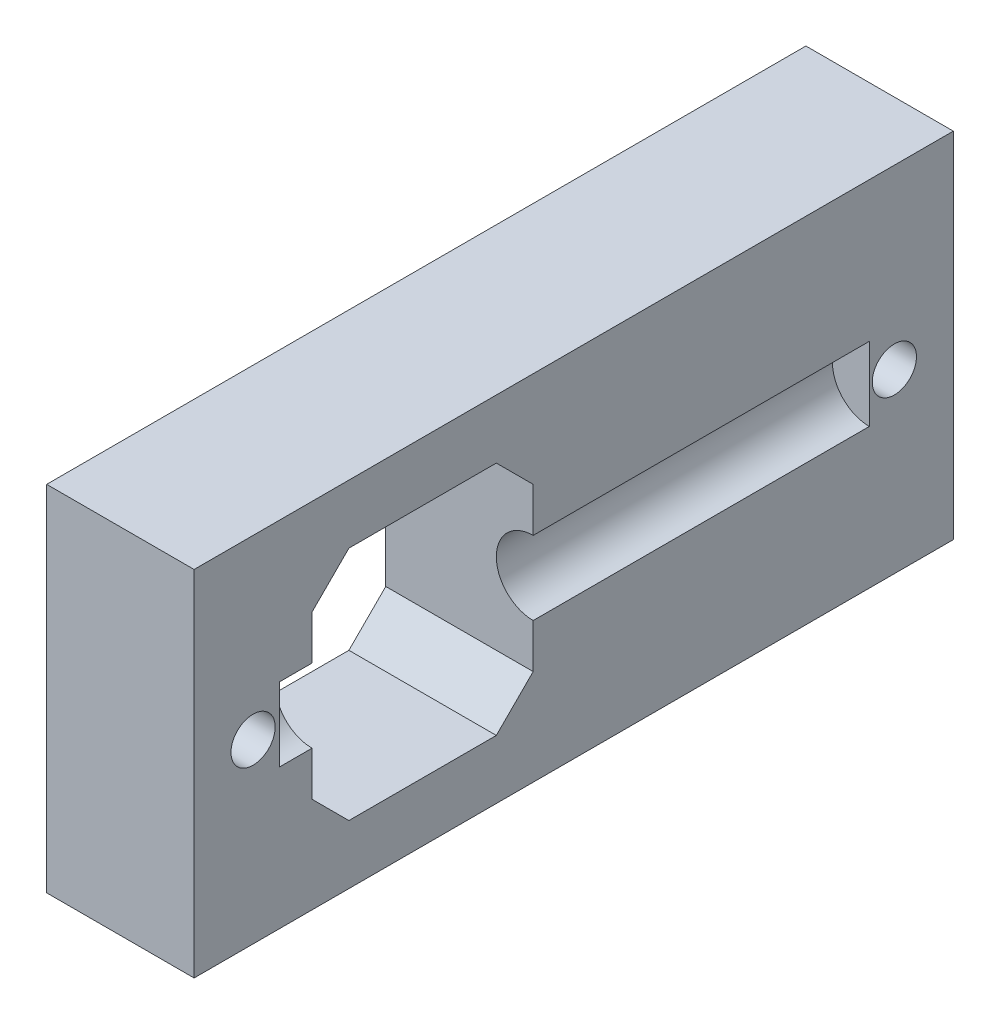
SolidWorks part; units mm, degrees
ref_plane "前基準面" through (0, 0, 0) normal (0, 0, 1) x (1, 0, 0)
ref_plane "上基準面" through (0, 0, 0) normal (0, 1, 0) x (1, 0, 0)
ref_plane "右基準面" through (0, 0, 0) normal (1, 0, 0) x (0, 0, -1)
sketch "草圖1" plane through (0, 0, 0) normal (0, 0, 1) x (1, 0, 0)
  line L1 (-21, 21) -> (21, 21)
  line L2 (-21, 21) -> (-21, -21)
  line L3 (-21, -21) -> (21, -21)
  line L4 (21, 21) -> (21, -21)
  point P4 (0, 21)
  point P6 (-21, 0)
  dimension "D1" = 42
  dimension "D2" = 42
extrude "填料-伸長1" add sketch "草圖1" along normal blind 40
chamfer "導角1" distance 5 angle 45 4 edges at (-21, -21, 20) (21, -21, 20) (21, 21, 20) (-21, 21, 20)
sketch "草圖4" plane through (0, 0, 40) normal (0, 0, 1) x (1, 0, 0)
  line L0 (-21, 16) -> (-21, -16) construction
  line L1 (16, 21) -> (-16, 21) construction
  line L2 (0, 21) -> (0, -21) construction
  line L3 (-16, -21) -> (16, -21) construction
  line L4 (0, -21) -> (21, 0) construction
  line L5 (21, -16) -> (21, 16) construction
  line L6 (21, 0) -> (-21, 0) construction
  circle A0 centre (-15.5, 15.5) radius 1.75
  circle A1 centre (-15.5, -15.5) radius 1.75
  circle A2 centre (15.5, -15.5) radius 1.75
  circle A3 centre (15.5, 15.5) radius 1.75
  dimension "D1" = 3.5
  dimension "D2" = 5.5
  dimension "D3" = 5.5
  dimension "D4" = 31
extrude "除料-伸長1" cut sketch "草圖4" against normal blind 3
sketch "草圖5" plane through (-21, 0, 0) normal (-1, 0, 0) x (0, 0, 1)
  line L0 (40, 16) -> (40, -16) construction
  line L1 (40, 12) -> (66, 12)
  line L2 (40, 12) -> (40, -12)
  line L3 (40, -12) -> (66, -12)
  line L4 (66, 12) -> (66, -12)
  line L5 (0, 0) -> (66, 0) construction
  line L7 (43, 8) -> (58, 8)
  line L8 (43, 8) -> (43, -8)
  line L9 (43, -8) -> (58, -8)
  line L10 (58, 8) -> (58, -8)
  dimension "D1" = 24
  dimension "D2" = 26
  dimension "D3" = 4
  dimension "D4" = 8
  dimension "D5" = 3
  dimension "D6" = 4
extrude "填料-伸長2" add sketch "草圖5" against normal blind 21 separate body
sketch "草圖7" plane through (21, 0, 0) normal (1, 0, 0) x (0, 0, -1)
  line L0 (0, -16) -> (0, 16) construction
  line L1 (-40, 12) -> (0, 12)
  line L2 (-40, 12) -> (-40, -12)
  line L3 (-40, -12) -> (0, -12)
  line L4 (0, 12) -> (0, -12)
extrude "除料-伸長3" cut sketch "草圖7" against normal blind 21
sketch "草圖6" plane through (0, 0, 0) normal (1, 0, 0) x (0, 0, -1)
  line L3 (-58, 8) -> (-66, 8) construction
  line L4 (-66, -12) -> (-66, 12) construction
  line L5 (-58, -8) -> (-66, -8) construction
  line L6 (-62, 8) -> (-62, -8) construction
  line L7 (-60.25, 0) -> (-20.25, 0) construction
  circle A0 centre (-62, 0) radius 3
  circle A1 centre (-62, 0) radius 1.75 construction
  circle A2 centre (-18.5, 0) radius 1.75 construction
  circle A3 centre (-18.5, 0) radius 3
  dimension "D1" = 6
  dimension "D4" = 3.5
  dimension "D3" = 3.5
  dimension "D5" = 6
  dimension "D2" = 40
extrude "除料-伸長2" cut sketch "草圖6" against normal blind 10
chamfer "導角2" distance 2.5 angle 45 4 edges at (-10.5, -8, 43) (-10.5, 8, 43) (-10.5, -8, 58) (-10.5, 8, 58)
sketch "草圖8" plane through (0, 0, 0) normal (1, 0, 0) x (0, 0, -1)
  line L0 (-40, -12) -> (0, -12) construction
  line L1 (-66, 12) -> (-14.5, 12)
  line L2 (-66, 12) -> (-66, -12)
  line L3 (-66, -12) -> (-14.5, -12)
  line L4 (-14.5, 12) -> (-14.5, -12)
  line L5 (-58, 5.5) -> (-58, -5.5)
  line L6 (-58, -5.5) -> (-55.5, -8)
  line L7 (-55.5, -8) -> (-45.5, -8)
  line L8 (-45.5, -8) -> (-43, -5.5)
  line L9 (-43, -5.5) -> (-43, 5.5)
  line L10 (-43, 5.5) -> (-45.5, 8)
  line L11 (-45.5, 8) -> (-55.5, 8)
  line L12 (-55.5, 8) -> (-58, 5.5)
  circle A0 centre (-62, 0) radius 3 construction
  circle A1 centre (-62, 0) radius 3 construction
  circle A2 centre (-18.5, 0) radius 3 construction
  circle A3 centre (-18.5, 0) radius 3 construction
  circle A4 centre (-62, 0) radius 1.5
  circle A5 centre (-18.5, 0) radius 1.5
  point P9 (-65, 0)
  point P10 (-66, 0)
  point P13 (-15.5, 0)
  dimension "D1" = 3
  dimension "D4" = 3
  dimension "D2" = 1
  dimension "D3" = 1
extrude "填料-伸長3" add sketch "草圖8" along normal blind 10
sketch "草圖9" plane through (0, 0, 66) normal (0, 0, 1) x (1, 0, 0)
  line L0 (21, 12) -> (21, 16)
  line L1 (21, 16) -> (16, 21)
  line L2 (16, 21) -> (-16, 21)
  line L3 (-16, 21) -> (-21, 16)
  line L4 (-21, 16) -> (-21, -16)
  line L5 (-21, -16) -> (-16, -21)
  line L6 (-16, -21) -> (16, -21)
  line L7 (16, -21) -> (21, -16)
  line L8 (21, -16) -> (21, -12)
  line L9 (21, 12) -> (0, 12)
  line L11 (10, 12) -> (-21, 12) construction
  line L13 (0, 12) -> (0, -12)
  line L14 (10, -12) -> (-21, -12) construction
  line L15 (0, -12) -> (21, -12)
extrude "除料-伸長5" cut sketch "草圖9" against normal through all
sketch "草圖10" plane through (0, 0, 66) normal (0, 0, 1) x (1, 0, 0)
  line L0 (10, 12) -> (10, -12) construction
  circle A0 centre (10, 0) radius 2.5
  dimension "D1" = 5
extrude "除料-伸長6" cut sketch "草圖10" against normal blind 40 from offset 5.8
